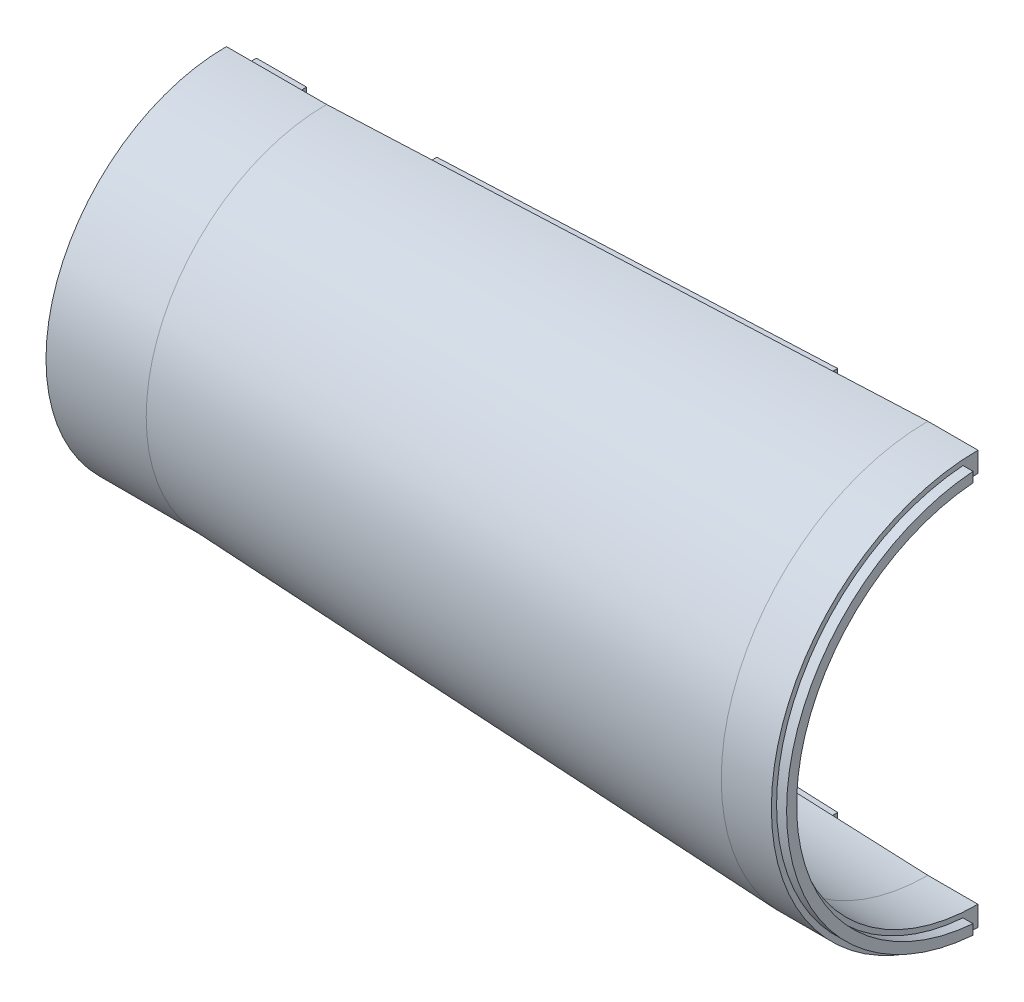
SolidWorks part; units mm, degrees
ref_plane "Front Plane" through (0, 0, 0) normal (0, 0, 1) x (1, 0, 0)
ref_plane "Top Plane" through (0, 0, 0) normal (0, 1, 0) x (1, 0, 0)
ref_plane "Right Plane" through (0, 0, 0) normal (1, 0, 0) x (0, 0, -1)
sketch "Sketch2" plane through (0, 0, 0) normal (0, 0, 1) x (1, 0, 0)
  line L0 (0, 0) -> (0, 40.64)
  line L1 (0, 0) -> (5.08, 0)
  line L2 (5.08, 0) -> (5.08, 40.64)
  line L3 (0, 40.64) -> (0, 45.72)
  line L4 (0, 45.72) -> (25.4, 45.72)
  line L6 (5.08, 40.64) -> (25.4, 40.64)
  line L8 (190.5, 52.3739) -> (177.8, 52.3739)
  line L9 (177.8, 52.3739) -> (25.4, 45.72)
  line L10 (190.5, 47.2939) -> (177.8, 47.2939)
  line L11 (177.8, 47.2939) -> (25.4, 40.64)
  line L12 (190.5, 52.3739) -> (190.5, 47.2939)
  dimension "D8" = 5.08
  dimension "D1" = 40.64
  dimension "D2" = 5.08
  dimension "D3" = 40.64
  dimension "D4" = 5.08
  dimension "D5" = 25.4
  dimension "D6" = 152.4
  dimension "D7" = 12.7
  dimension "D9" = 182.5
  dimension "D10" = 12.7
revolve "Revolve2" add sketch "Sketch2" angle 180 about L1
sketch "Sketch4" plane through (0, 0, 0) normal (-1, 0, 0) x (0, 0, 1)
  line L0 (0, -45.72) -> (0, 45.72) construction
  line L1 (0, 0) -> (20.32, 0)
  line L2 (0, -20.32) -> (0, 20.32)
  line L3 (0, 20.32) -> (20.32, 20.32)
  line L4 (20.32, -20.32) -> (20.32, 20.32)
  line L5 (0, -20.32) -> (20.32, -20.32)
  line M6 (0, 45.72) -> (0, -45.72)
  dimension "D1" = 20.32
  dimension "D2" = 20.32
extrude "Cut-Extrude2" cut sketch "Sketch4" against normal blind 32.004 contours L1 L4 L3 M6 | L5 L4 L1 M6
sketch "Sketch5" plane through (0, 0, 0) normal (0, 0, -1) x (-1, 0, 0)
  line L0 (-5.08, 40.64) -> (0, 40.64) construction
  line L1 (-3.81, 40.64) -> (-1.27, 40.64)
  line L2 (-3.81, 40.64) -> (-3.81, 27.94)
  line L3 (-3.81, 27.94) -> (-1.27, 27.94)
  line L4 (-1.27, 40.64) -> (-1.27, 27.94)
  line L5 (0, 20.32) -> (0, 45.72) construction
  line L6 (-5.08, 40.64) -> (-5.08, 45.72) construction
  line L7 (-25.4, 45.72) -> (0, 45.72) construction
  line L8 (-152.4, 49.9949) -> (-152.4, 47.4549)
  line L9 (-5.08, 44.45) -> (-17.78, 44.45)
  line L10 (-5.08, 44.45) -> (-5.08, 41.91)
  line L11 (-5.08, 41.91) -> (-17.78, 41.91)
  line L12 (-17.78, 44.45) -> (-17.78, 41.91)
  line L13 (-152.4, 47.4549) -> (-50.8, 43.019)
  line L14 (-50.8, 43.019) -> (-50.8, 45.559)
  line L15 (-50.8, 45.559) -> (-152.4, 49.9949)
  line L16 (-177.8, 52.3739) -> (-25.4, 45.72) construction
  line L17 (-50.8, 45.559) -> (-50.8, 46.829) construction
  line L18 (-50.8, 43.019) -> (-50.8, 41.749) construction
  line L19 (-25.4, 40.64) -> (-177.8, 47.2939) construction
  line L20 (-152.4, 46.1849) -> (-152.4, 47.4549) construction
  line L21 (-152.4, 49.9949) -> (-152.4, 51.2649) construction
  line L22 (0, 0) -> (-190.5, 0) construction
  line L23 (-190.5, 47.2939) -> (-190.5, -47.2939) construction
  line L24 (-50.8, -43.019) -> (-50.8, -45.559)
  line L25 (-152.4, -47.4549) -> (-50.8, -43.019)
  line L26 (-152.4, -49.9949) -> (-152.4, -47.4549)
  line L27 (-50.8, -45.559) -> (-152.4, -49.9949)
  line L28 (-5.08, -41.91) -> (-17.78, -41.91)
  line L29 (-17.78, -44.45) -> (-17.78, -41.91)
  line L30 (-5.08, -44.45) -> (-17.78, -44.45)
  line L31 (-5.08, -44.45) -> (-5.08, -41.91)
  line L32 (-3.81, -27.94) -> (-1.27, -27.94)
  line L33 (-1.27, -40.64) -> (-1.27, -27.94)
  line L34 (-3.81, -40.64) -> (-1.27, -40.64)
  line L35 (-3.81, -40.64) -> (-3.81, -27.94)
  point P9 (-2.54, 40.64)
  point P10 (-2.54, 40.64)
  point P18 (-5.08, 43.18)
  point P19 (-5.08, 43.18)
  point P26 (-101.6, 49.047)
  point P27 (-101.6, 47.777)
  dimension "D1" = 12.7
  dimension "D2" = 2.54
  dimension "D3" = 12.7
  dimension "D4" = 2.54
  dimension "D5" = 2.54
  dimension "D6" = 2.54
  dimension "D7" = 101.6
extrude "Boss-Extrude1" add sketch "Sketch5" along normal blind 2.54 contours L15 L8 L13 L14 | L10 L9 L12 L11 | L2 L1 L4 L3 | L32 L33 L34 L35 | L28 L29 L30 L31 | L24 L27 L26 L25
sketch "Sketch6" plane through (190.5, 0, 0) normal (1, 0, 0) x (0, 0, -1)
  line L0 (-3.81, 50.9116) -> (-3.81, 48.3716)
  line L1 (0, 52.3739) -> (0, 47.2939) construction
  line L2 (0, 0) -> (-52.3739, 0) construction
  line L3 (-3.81, -50.9116) -> (-3.81, -48.3716)
  arc A0 (-3.81, 50.9116) -> (-3.81, -50.9116) centre (0, 0) ccw
  arc A1 (-3.81, 48.3716) -> (-3.81, -48.3716) centre (0, 0) ccw
  arc A2 (0, 52.3739) -> (0, -52.3739) centre (0, 0) ccw construction
  dimension "D3" = 51.054
  dimension "D1" = 2.54
  dimension "D2" = 3.81
extrude "Boss-Extrude2" add sketch "Sketch6" along normal blind 2.54 contours A0 L3 A1 L0
